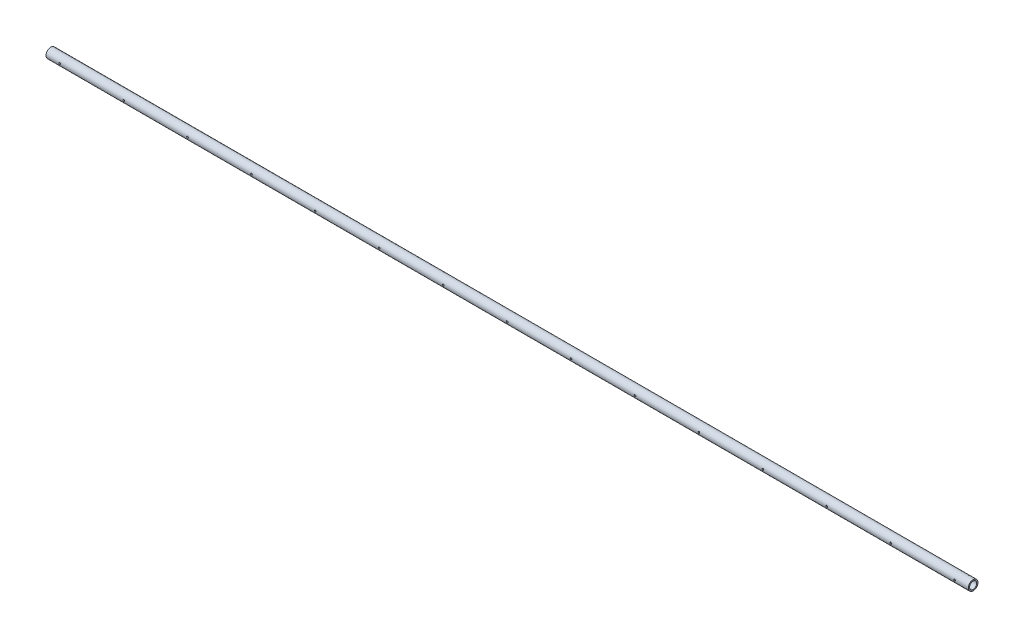
SolidWorks part; units mm, degrees
material "AISI 316  (SS)"
ref_plane "Front Plane" through (0, 0, 0) normal (0, 0, 1) x (1, 0, 0)
ref_plane "Top Plane" through (0, 0, 0) normal (0, 1, 0) x (1, 0, 0)
ref_plane "Right Plane" through (0, 0, 0) normal (1, 0, 0) x (0, 0, -1)
sketch "Sketch1" plane through (0, 0, 0) normal (1, 0, 0) x (0, 0, -1)
  circle A0 centre (0, 0) radius 10.65
  circle A1 centre (0, 0) radius 7.88
  dimension "D1" = 21.3
  dimension "D2" = 2.77
extrude "Boss-Extrude1" add sketch "Sketch1" along normal blind 2020
sketch "Sketch2" plane through (0, 0, 0) normal (0, 0, 1) x (1, 0, 0)
  line L0 (2020, -10.65) -> (2020, 10.65) construction
  circle A0 centre (1990, 0) radius 1.85
  dimension "D1" = 3.7
  dimension "D2" = 30
extrude "Cut-Extrude1" cut sketch "Sketch2" along normal blind 40
pattern_linear "LPattern1" count 15 spacing 140 along (-1, 0, 0) of "Cut-Extrude1"
